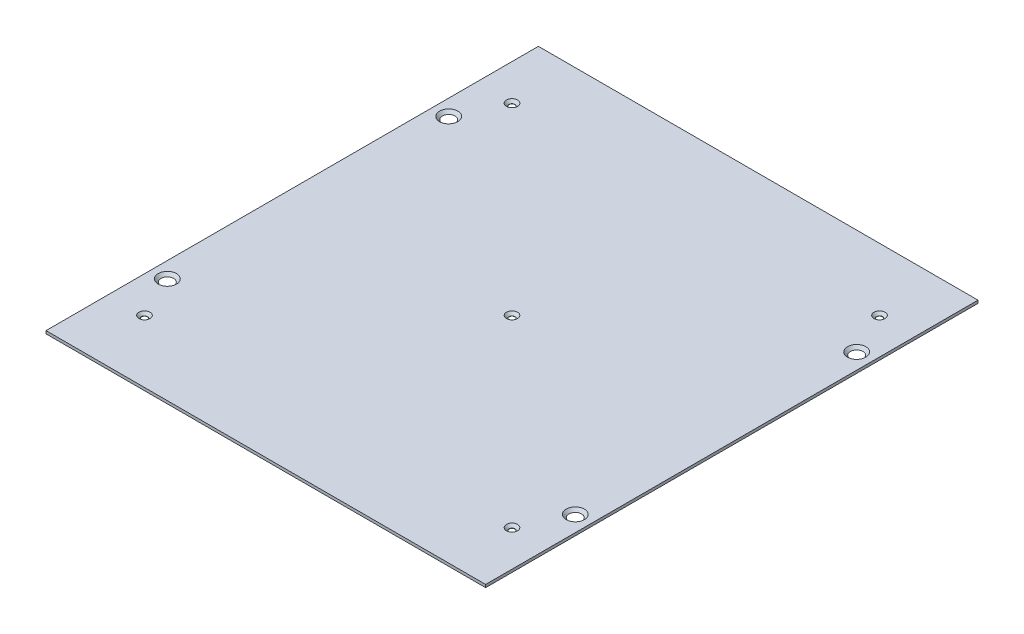
SolidWorks part; units mm, degrees
material "Copper"
ref_plane "Front Plane" through (0, 0, 0) normal (0, 0, 1) x (1, 0, 0)
ref_plane "Top Plane" through (0, 0, 0) normal (0, 1, 0) x (1, 0, 0)
ref_plane "Right Plane" through (0, 0, 0) normal (1, 0, 0) x (0, 0, -1)
sketch "Sketch1" plane through (0, 0, 0) normal (0, 1, 0) x (1, 0, 0)
  line L1 (-125, 140) -> (125, 140)
  line L2 (-125, 140) -> (-125, -140)
  line L3 (-125, -140) -> (125, -140)
  line L4 (125, 140) -> (125, -140)
  line L5 (-125, 140) -> (125, -140) construction
  line L6 (-125, -140) -> (125, 140) construction
  point P0 (0, 0)
  dimension "D1" = 250
  dimension "D2" = 280
extrude "Boss-Extrude1" add sketch "Sketch1" along normal blind 1.6
hole_wizard "CSK for M5 Flat Head Machine Screw1" positions "Sketch3" profile "Sketch2" countersink size "M5" standard "Ansi Metric" end condition through all
sketch "Sketch3" plane through (0, 1.6, 0) normal (0, 1, 0) x (-1, 0, 0)
  circle A0 centre (116, -80) radius 3 construction
  circle A1 centre (-116, -80) radius 3 construction
  circle A2 centre (116, 80) radius 3 construction
  circle A3 centre (-116, 80) radius 3 construction
  point P0 (116, -80)
  point P1 (-116, -80)
  point P3 (-116, 80)
  point P5 (116, 80)
sketch "Sketch2" plane through (-116, 1.6, -80) normal (1, 0, 0) x (0, 0, 1)
  line L0 (0, 0) -> (0, 1.6)
  line L1 (0, 1.6) -> (2.75, 1.6)
  line L2 (2.75, 1.6) -> (2.75, 2.45)
  line L3 (2.75, 2.45) -> (5.2, 0)
  line L5 (5.2, 0) -> (0, 0)
  line L6 (-2.75, 2.45) -> (-5.2, 0) construction
  line L11 (0, -6.35) -> (0, 107.95) construction
  dimension "Thru Hole Dia." = 5.5
  dimension "Thru Hole Depth" = 1.6
  dimension "Near C'Sink Dia." = 10.4
  dimension "Near C'Sink Angle" = 90
hole_wizard "CSK for M3 Flat Head Machine Screw1" positions "Sketch5" profile "Sketch4" countersink size "M3" standard "Ansi Metric" end condition through all
sketch "Sketch5" plane through (0, 1.6, 0) normal (0, 1, 0) x (-1, 0, 0)
  circle A0 centre (104.5, -104.5) radius 1.5 construction
  circle A1 centre (104.5, 104.5) radius 1.5 construction
  circle A2 centre (-104.5, 104.5) radius 1.5 construction
  circle A3 centre (-104.5, -104.5) radius 1.5 construction
  circle A4 centre (0, 0) radius 1.25 construction
  point P0 (0, 0)
  point P1 (104.5, 104.5)
  point P3 (-104.5, 104.5)
  point P5 (-104.5, -104.5)
  point P7 (104.5, -104.5)
sketch "Sketch4" plane through (0, 1.6, 0) normal (1, 0, 0) x (0, 0, 1)
  line L0 (0, 0) -> (0, 1.6)
  line L1 (0, 1.6) -> (1.7, 1.6)
  line L2 (1.7, 1.6) -> (1.7, 1.45)
  line L3 (1.7, 1.45) -> (3.15, 0)
  line L5 (3.15, 0) -> (0, 0)
  line L6 (-1.7, 1.45) -> (-3.15, 0) construction
  line L11 (0, -6.35) -> (0, 107.95) construction
  dimension "Thru Hole Dia." = 3.4
  dimension "Thru Hole Depth" = 1.6
  dimension "Near C'Sink Dia." = 6.3
  dimension "Near C'Sink Angle" = 90
